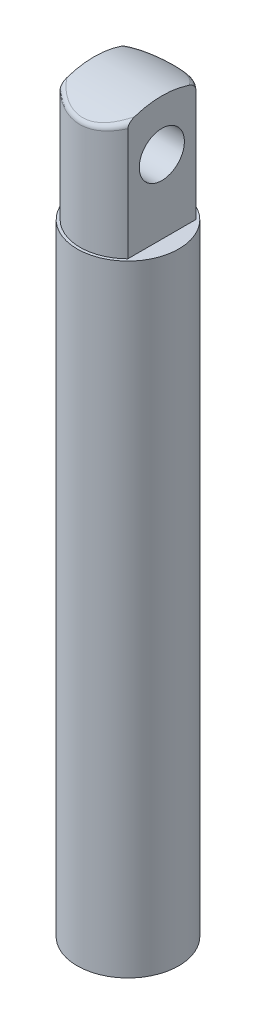
SolidWorks part; units mm, degrees
material "1350 合金"
ref_plane "前视基准面" through (0, 0, 0) normal (0, 0, 1) x (1, 0, 0)
ref_plane "上视基准面" through (0, 0, 0) normal (0, 1, 0) x (1, 0, 0)
ref_plane "右视基准面" through (0, 0, 0) normal (1, 0, 0) x (0, 0, -1)
sketch "草图1" plane through (0, 0, 0) normal (0, 1, 0) x (1, 0, 0)
  circle A0 centre (0, 0) radius 4.5
  dimension "D1" = 9
extrude "凸台-拉伸1" add sketch "草图1" along normal blind 55
sketch "草图2" plane through (0, 55, 0) normal (0, 1, 0) x (1, 0, 0)
  line L0 (0, 4.25) -> (0, -5.0818) construction
  line L1 (-3, 3.0104) -> (-3, -3.0104)
  line L2 (3, 3.0104) -> (3, -3.0104)
  line L4 (-3, 4.8439) -> (-3, -5.0818) construction
  line L5 (0, 4.8439) -> (0, -5.0818) construction
  line L6 (3, 4.8439) -> (3, -5.0818) construction
  arc A0 (-3, -3.0104) -> (3, -3.0104) centre (0, 0) ccw
  arc A1 (3, 3.0104) -> (-3, 3.0104) centre (0, 0) ccw
  dimension "D1" = 8.5
  dimension "D2" = 3
  dimension "D3" = 3
extrude "凸台-拉伸2" add sketch "草图2" along normal blind 15
sketch "草图4" plane through (-3, 0, 0) normal (-1, 0, 0) x (0, 0, 1)
  line L0 (0, 55) -> (0, 61.5) construction
  line L1 (4.5, 55) -> (-4.5, 55) construction
  circle A0 centre (0, 61.5) radius 2
  dimension "D2" = 4
  dimension "D1" = 6.5
extrude "切除-拉伸1" cut sketch "草图4" against normal through all
sketch "草图5" plane through (-3, 0, 0) normal (-1, 0, 0) x (0, 0, 1)
  line L0 (0, 61.5) -> (0, 58.5) construction
  line L1 (-4.8133, 64.2517) -> (-4.8133, 72.4064)
  line L2 (-4.8133, 72.4064) -> (5.4669, 72.4064)
  line L3 (5.4669, 72.4064) -> (5.4669, 63.6345)
  arc A1 (5.4669, 63.6345) -> (-4.8133, 64.2517) centre (0, 58.5) ccw
  dimension "D1" = 3
  dimension "D2" = 15
extrude "切除-拉伸3" cut sketch "草图5" against normal through all
fillet "圆角1" radius 0.5 2 edges at (-0.4387, 64.6952, -4.2273) (0.4387, 64.6952, 4.2273)
